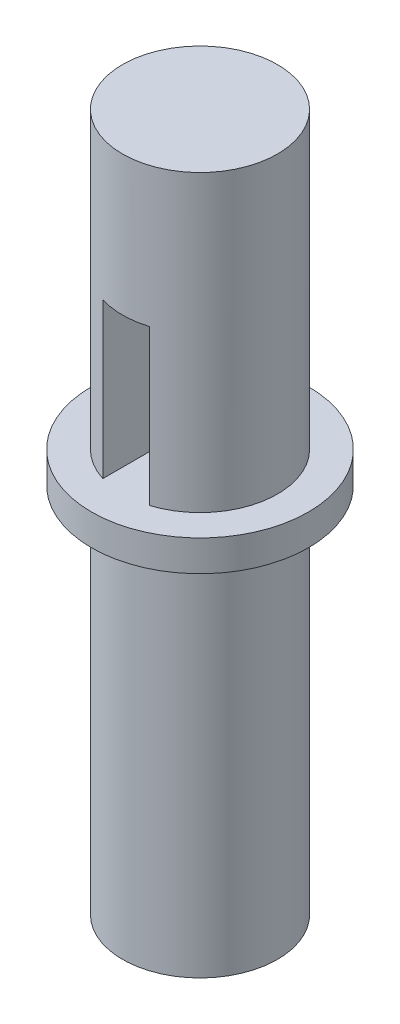
SolidWorks part; units mm, degrees
ref_plane "Front Plane" through (0, 0, 0) normal (0, 0, 1) x (1, 0, 0)
ref_plane "Top Plane" through (0, 0, 0) normal (0, 1, 0) x (1, 0, 0)
ref_plane "Right Plane" through (0, 0, 0) normal (1, 0, 0) x (0, 0, -1)
sketch "Sketch1" plane through (0, 0, 0) normal (0, 1, 0) x (1, 0, 0)
  circle A0 centre (1.6099, 0) radius 5
extrude "Boss-Extrude1" add sketch "Sketch1" along normal blind 60
sketch "Sketch2" plane through (0, 0, 0) normal (0, 0, 1) x (1, 0, 0)
  line L0 (1.6099, 60) -> (1.6099, 46)
  line L1 (6.6099, 60) -> (-3.3901, 60) construction
  line L3 (0.1099, 41) -> (3.1099, 41)
  line L4 (0.1099, 41) -> (0.1099, 51)
  line L5 (0.1099, 51) -> (3.1099, 51)
  line L6 (3.1099, 41) -> (3.1099, 51)
  line L7 (0.1099, 41) -> (3.1099, 51) construction
  line L8 (0.1099, 51) -> (3.1099, 41) construction
  dimension "D1" = 3
  dimension "D2" = 10
extrude "Cut-Extrude2" cut sketch "Sketch2" against normal mid plane 60 contours L5 L6 L3 L4
sketch "Sketch3" plane through (0, 0, 0) normal (0, -1, 0) x (1, 0, 0)
  circle A0 centre (1.6099, 0) radius 5 construction
  circle A1 centre (1.6099, 0) radius 5
extrude "Cut-Extrude3" cut sketch "Sketch3" against normal blind 15
sketch "Sketch4" plane through (0, 15, 0) normal (0, -1, 0) x (1, 0, 0)
  circle A0 centre (1.6099, 0) radius 7
extrude "Boss-Extrude2" add sketch "Sketch4" along normal blind 2 from offset 26
